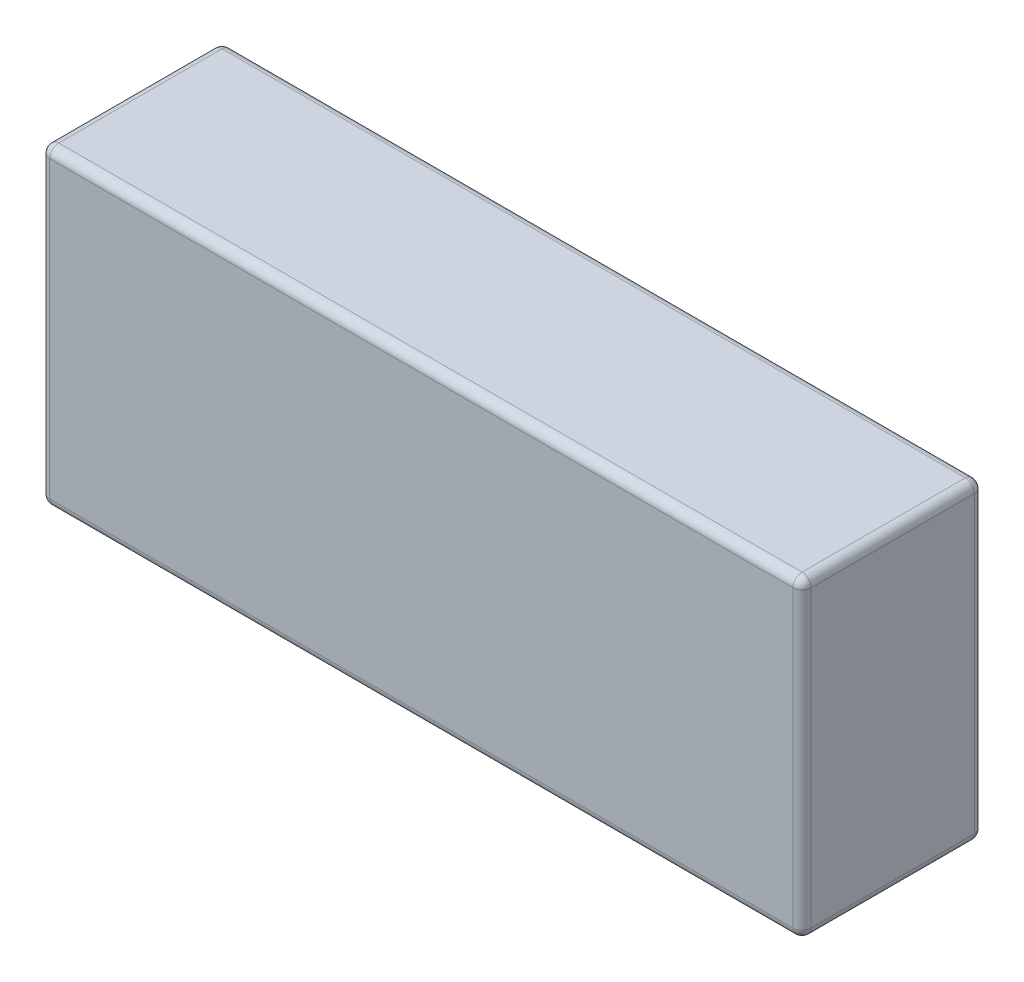
SolidWorks part; units mm, degrees
ref_plane "Front Plane" through (0, 0, 0) normal (0, 0, 1) x (1, 0, 0)
ref_plane "Top Plane" through (0, 0, 0) normal (0, 1, 0) x (1, 0, 0)
ref_plane "Right Plane" through (0, 0, 0) normal (1, 0, 0) x (0, 0, -1)
sketch "Sketch1" plane through (0, 0, 0) normal (0, 1, 0) x (1, 0, 0)
  line L0 (0, 0) -> (0, -40)
  line L1 (0, -40) -> (168, -40)
  line L2 (168, -40) -> (168, 0)
  line L3 (168, 0) -> (0, 0)
  dimension "D1" = 168
  dimension "D2" = 40
extrude "Boss-Extrude1" add sketch "Sketch1" along normal blind 69
fillet "Fillet1" radius 2 12 edges at (0, 34.5, 0) (0, 34.5, 40) (168, 34.5, 40) (168, 34.5, 0) (168, 69, 20) (84, 69, 40) (0, 69, 20) (84, 69, 0) (168, 0, 20) (84, 0, 40) (0, 0, 20) (84, 0, 0)
